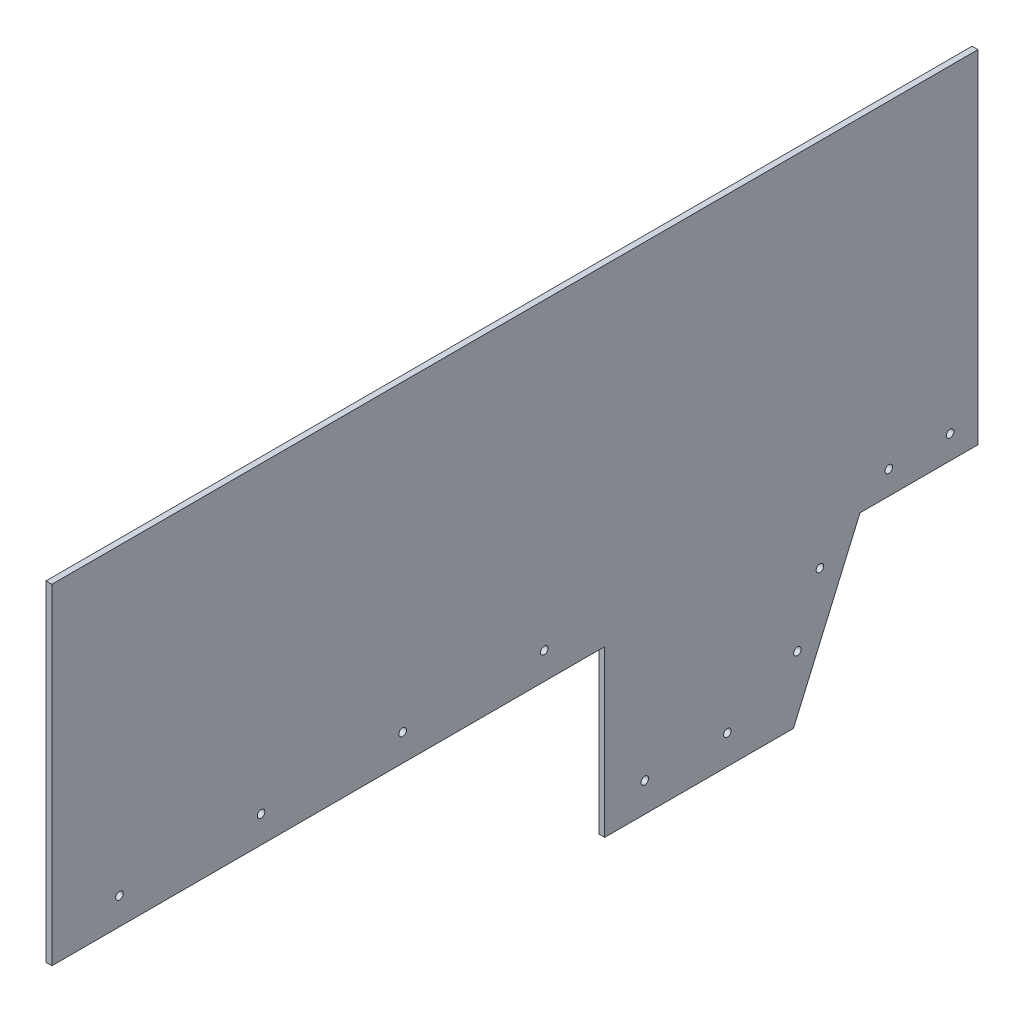
SolidWorks part; units mm, degrees
material "6061-T6 (SS)"
ref_plane "X-Y Datum" through (0, 0, 0) normal (0, 0, 1) x (1, 0, 0)
ref_plane "X-Z Datum" through (0, 0, 0) normal (0, 1, 0) x (1, 0, 0)
ref_plane "Y-Z Datum" through (0, 0, 0) normal (1, 0, 0) x (0, 0, -1)
sketch "Sketch1" plane through (0, 0, 0) normal (1, 0, 0) x (0, 0, -1)
  line L1 (-249.174, 88.9) -> (249.174, 88.9)
  line L2 (-249.174, 88.9) -> (-249.174, -88.9)
  line L3 (-249.174, -88.9) -> (249.174, -88.9)
  line L4 (249.174, 88.9) -> (249.174, -88.9)
  line L5 (-249.174, 88.9) -> (249.174, -88.9) construction
  line L6 (-249.174, -88.9) -> (249.174, 88.9) construction
  point P0 (0, 0)
  dimension "D1" = 177.8
  dimension "D2" = 498.348
extrude "Boss-Extrude1" add sketch "Sketch1" along normal mid plane 3.175
sketch "Sketch2" plane through (1.5875, 0, 0) normal (1, 0, 0) x (0, 0, -1)
  line L0 (249.174, -88.9) -> (249.174, -95.25)
  line L1 (249.174, -95.25) -> (185.674, -95.25)
  line L2 (185.674, -95.25) -> (149.8854, -177.8)
  line L3 (149.8854, -177.8) -> (48.2854, -177.8)
  line L4 (48.2854, -177.8) -> (48.2854, -88.9)
  line L5 (-249.174, -88.9) -> (249.174, -88.9) construction
  line L6 (48.2854, -88.9) -> (249.174, -88.9)
  line L8 (48.2854, -76.2) -> (48.2854, 88.9)
  line L10 (249.174, -88.9) -> (249.174, 88.9) construction
  line M10 (-249.174, -88.9) -> (249.174, -88.9)
  dimension "D1" = 6.35
  dimension "D2" = 63.5
  dimension "D3" = 88.9
  dimension "D4" = 101.6
extrude "Boss-Extrude2" add sketch "Sketch2" against normal blind 3.175 contours L4 L3 L2 L1 L0 M10
sketch "Sketch3" plane through (1.5875, 0, 0) normal (1, 0, 0) x (0, 0, -1)
  line L2 (48.2854, -74.3635) -> (15.7854, -74.3635)
  line L5 (48.2854, -88.9) -> (48.2854, -59.827)
  circle A1 centre (15.7854, -74.3635) radius 2.025
extrude "Cut-Extrude1" cut sketch "Sketch3" against normal through all
pattern_linear "LPattern1" count 4 spacing 76.2 along (0, 0, 1) of "Cut-Extrude1"
sketch "Sketch4" plane through (-1.5875, 0, 0) normal (-1, 0, 0) x (0, 0, 1)
  line L0 (-69.8754, -177.8) -> (-69.8754, -162.052)
  line L2 (-149.8854, -177.8) -> (-48.2854, -177.8) construction
  line L3 (-48.2854, -162.052) -> (-69.8754, -162.052)
  line L4 (-48.2854, -177.8) -> (-48.2854, -88.9) construction
  circle A0 centre (-69.8754, -162.052) radius 2.025
extrude "Cut-Extrude2" cut sketch "Sketch4" against normal through all contours L3 A0 L0 | L0 A0 L3
pattern_linear "LPattern2" count 2 spacing 44.45 along (0, 0, -1) of "Cut-Extrude2"
sketch "Sketch5" plane through (-1.5875, 0, 0) normal (-1, 0, 0) x (0, 0, 1)
  line L0 (-162.9577, -147.6475) -> (-152.0047, -142.8989)
  line L1 (-185.674, -95.25) -> (-149.8854, -177.8) construction
  circle A0 centre (-152.0047, -142.8989) radius 2.025
extrude "Cut-Extrude3" cut sketch "Sketch5" against normal through all
sketch "Sketch8" plane through (-1.5875, 0, 0) normal (-1, 0, 0) x (0, 0, 1)
  line L0 (-152.0047, -142.8989) -> (-167.6603, -112.0213)
  line L1 (-167.6603, -112.0213) -> (-164.1171, -110.2248)
  line L2 (-152.0047, -142.8989) -> (-161.6752, -150.6055)
  line L3 (-185.674, -95.25) -> (-149.8854, -177.8) construction
  circle A0 centre (-164.1171, -110.2248) radius 2.025
extrude "Cut-Extrude5" cut sketch "Sketch8" against normal through all
sketch "Sketch9" plane through (-1.5875, 0, 0) normal (-1, 0, 0) x (0, 0, 1)
  line L0 (-201.1707, -95.25) -> (-201.1707, -82.55)
  line L1 (-249.174, -95.25) -> (-185.674, -95.25) construction
  circle A0 centre (-201.1707, -82.55) radius 2.025
extrude "Cut-Extrude6" cut sketch "Sketch9" against normal through all
pattern_linear "LPattern4" count 2 spacing 33.02 along (0, 0, -1) of "Cut-Extrude6"
